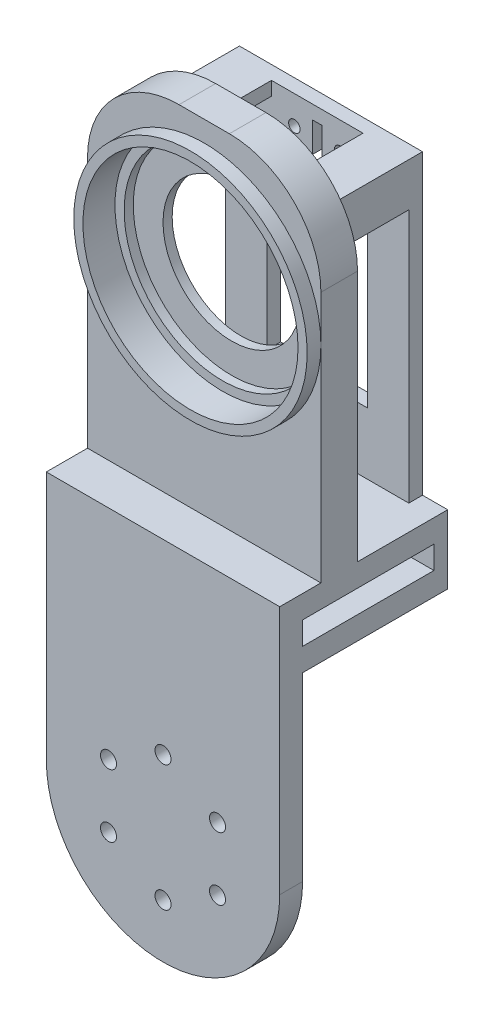
SolidWorks part; units mm, degrees
ref_plane "정면" through (0, 0, 0) normal (0, 0, 1) x (1, 0, 0)
ref_plane "윗면" through (0, 0, 0) normal (0, 1, 0) x (1, 0, 0)
ref_plane "우측면" through (0, 0, 0) normal (1, 0, 0) x (0, 0, -1)
sketch "스케치1" plane through (0, 0, 0) normal (0, 0, 1) x (1, 0, 0)
  line L2 (-25.5, 0) -> (-25.5, 54.5)
  line L3 (-25.5, 54.5) -> (25.5, 54.5)
  line L4 (25.5, 0) -> (25.5, 54.5)
  arc A0 (-25.5, 0) -> (25.5, 0) centre (0, 0) ccw
  dimension "D1" = 51
  dimension "D2" = 54.5
extrude "보스-돌출1" add sketch "스케치1" along normal blind 5
sketch "스케치2" plane through (0, 0, 0) normal (0, 0, -1) x (-1, 0, 0)
  circle A0 centre (0, 0) radius 17.5
  dimension "D1" = 35
extrude "컷-돌출1" cut sketch "스케치2" against normal blind 2
sketch "스케치3" plane through (0, 0, 2) normal (0, 0, -1) x (-1, 0, 0)
  circle A0 centre (0, 0) radius 13.75 construction
  circle A1 centre (0, 13.75) radius 1.75
  circle A2 centre (11.9078, 6.875) radius 1.75
  circle A3 centre (11.9078, -6.875) radius 1.75
  circle A4 centre (0, -13.75) radius 1.75
  circle A5 centre (-11.9078, -6.875) radius 1.75
  circle A6 centre (-11.9078, 6.875) radius 1.75
  point P17 (0, 0)
  dimension "D1" = 27.5
  dimension "D2" = 3.5
  dimension "D3" = 6
extrude "컷-돌출2" cut sketch "스케치3" against normal through all
sketch "스케치4" plane through (0, 0, 0) normal (0, 0, -1) x (-1, 0, 0)
  line L0 (25.5, 54.5) -> (25.5, 0) construction
  line L1 (-25.5, 54.5) -> (25.5, 54.5)
  line L2 (-25.5, 54.5) -> (-25.5, 49.5)
  line L3 (-25.5, 39.5) -> (25.5, 39.5)
  line L4 (25.5, 54.5) -> (25.5, 49.5)
  line L5 (-25.5, 44.5) -> (25.5, 44.5)
  line L6 (-25.5, 49.5) -> (25.5, 49.5)
  line L7 (-25.5, 44.5) -> (-25.5, 39.5)
  line L8 (25.5, 44.5) -> (25.5, 39.5)
  dimension "D1" = 15
  dimension "D2" = 10
  dimension "D3" = 10
extrude "보스-돌출2" add sketch "스케치4" along normal blind 31.7
sketch "스케치12" plane through (0, 54.5, 0) normal (0, 1, 0) x (1, 0, 0)
  line L0 (-25.5, -5) -> (-25.5, 31.7) construction
  line L1 (-25.5, 4) -> (25.5, 4)
  line L2 (-25.5, 4) -> (-25.5, 12)
  line L3 (-25.5, 12) -> (25.5, 12)
  line L4 (25.5, 4) -> (25.5, 12)
  line L5 (25.5, -5) -> (25.5, 31.7) construction
  line L6 (25.5, -5) -> (-25.5, -5) construction
  dimension "D1" = 8
  dimension "D2" = 9
extrude "보스-돌출7" add sketch "스케치12" along normal blind 75
fillet "필렛2" radius 20 2 edges at (-25.5, 129.5, -8) (25.5, 129.5, -8)
sketch "스케치13" plane through (0, 0, -12) normal (0, 0, -1) x (-1, 0, 0)
  line L0 (0, 129.5) -> (0, 54.5) construction
  line L1 (-5.5, 129.5) -> (5.5, 129.5) construction
  line L2 (25.5, 54.5) -> (-25.5, 54.5) construction
  circle A0 centre (0, 99.5) radius 15
  dimension "D1" = 30
  dimension "D2" = 30
extrude "컷-돌출6" cut sketch "스케치13" against normal up to next
sketch "스케치14" plane through (0, 0, -4) normal (0, 0, 1) x (1, 0, 0)
  circle A0 centre (0, 99.5) radius 25.5
extrude "보스-돌출8" add sketch "스케치14" along normal blind 3
sketch "스케치16" plane through (0, 0, -1) normal (0, 0, 1) x (1, 0, 0)
  circle A0 centre (0, 99.5) radius 23.5
  circle A1 centre (0, 99.5) radius 25.5 construction
  dimension "D1" = 2
extrude "컷-돌출7" cut sketch "스케치16" against normal blind 7
sketch "스케치17" plane through (0, 0, -8) normal (0, 0, 1) x (1, 0, 0)
  circle A0 centre (0, 99.5) radius 21.5
  circle A1 centre (0, 99.5) radius 23.5 construction
  dimension "D1" = 2
extrude "컷-돌출8" cut sketch "스케치17" against normal blind 2
sketch "스케치18" plane through (0, 0, -12) normal (0, 0, -1) x (-1, 0, 0)
  line L1 (-20, 79.5) -> (20, 79.5) construction
  line L2 (-20, 79.5) -> (-20, 119.5) construction
  line L3 (-20, 119.5) -> (20, 119.5) construction
  line L4 (20, 79.5) -> (20, 119.5) construction
  line L5 (-20, 119.5) -> (-10, 119.5)
  line L6 (-20, 119.5) -> (-20, 110)
  line L7 (-20, 110) -> (-17, 110)
  line L8 (-10, 119.5) -> (-10, 116.5)
  line L9 (20, 119.5) -> (10, 119.5)
  line L10 (20, 119.5) -> (20, 110)
  line L11 (20, 110) -> (17, 110)
  line L12 (10, 119.5) -> (10, 116.5)
  line L15 (-10, 116.5) -> (-17, 116.5)
  line L16 (-17, 110) -> (-17, 116.5)
  line L19 (10, 116.5) -> (17, 116.5)
  line L20 (17, 110) -> (17, 116.5)
  point P0 (0, 99.5)
  dimension "D1" = 40
  dimension "D2" = 40
  dimension "D3" = 3
  dimension "D4" = 3
  dimension "D5" = 20
  dimension "D6" = 20
extrude "보스-돌출9" add sketch "스케치18" along normal blind 19.7
sketch "스케치19" plane through (0, 0, -31.7) normal (0, 0, -1) x (-1, 0, 0)
  line L0 (-25.5, 54.5) -> (25.5, 54.5) construction
  line L1 (-20, 119.5) -> (20, 119.5)
  line L2 (-20, 119.5) -> (-20, 54.5)
  line L4 (20, 119.5) -> (20, 54.5)
  line L5 (-20, 119.5) -> (-20, 110) construction
  line L6 (20, 110) -> (20, 119.5) construction
  line L7 (20, 54.5) -> (25.5, 54.5)
  line L8 (-25.5, 54.5) -> (-20, 54.5)
  line L9 (-25.5, 54.5) -> (-25.5, 39.5)
  line L10 (-25.5, 39.5) -> (25.5, 39.5)
  line L11 (25.5, 54.5) -> (25.5, 39.5)
extrude "보스-돌출10" add sketch "스케치19" against normal blind 3
sketch "스케치20" plane through (0, 0, -31.7) normal (0, 0, -1) x (-1, 0, 0)
  line L0 (0, 119.5) -> (0, 49.5) construction
  line L1 (20, 119.5) -> (-20, 119.5) construction
  line L2 (-25.5, 49.5) -> (25.5, 49.5) construction
  line L3 (1, 110) -> (11, 110)
  line L4 (-11, 110) -> (-1, 110)
  line L5 (-11, 110) -> (-11, 68)
  line L6 (-11, 68) -> (-1, 68)
  line L7 (11, 110) -> (11, 68)
  line L8 (-11, 110) -> (11, 68) construction
  line L9 (-11, 68) -> (11, 110) construction
  line L10 (-5, 113.35) -> (5, 113.35) construction
  line L11 (-5, 113.35) -> (-5, 64.75) construction
  line L12 (-5, 64.75) -> (5, 64.75) construction
  line L13 (5, 113.35) -> (5, 64.75) construction
  line L14 (-5, 113.35) -> (5, 64.75) construction
  line L15 (-5, 64.75) -> (5, 113.35) construction
  line L16 (-1, 116.5) -> (1, 116.5)
  line L17 (-1, 116.5) -> (-1, 110)
  line L19 (1, 116.5) -> (1, 110)
  line L20 (-1, 116.5) -> (1, 110) construction
  line L21 (-1, 110) -> (1, 116.5) construction
  line L22 (-1, 61.5) -> (1, 61.5)
  line L23 (-1, 61.5) -> (-1, 68)
  line L25 (1, 61.5) -> (1, 68)
  line L26 (-1, 61.5) -> (1, 68) construction
  line L27 (-1, 68) -> (1, 61.5) construction
  line L28 (1, 68) -> (11, 68)
  circle A0 centre (-5, 113.35) radius 1.25
  circle A1 centre (5, 113.35) radius 1.25
  circle A2 centre (-5, 64.75) radius 1.25
  circle A3 centre (5, 64.75) radius 1.25
  point P6 (0, 89)
  point P11 (0, 89.05)
  point P20 (0, 113.25)
  point P25 (0, 64.75)
  dimension "D7" = 2.5
  dimension "D1" = 22
  dimension "D2" = 42
  dimension "D3" = 9.5
  dimension "D4" = 3.35
  dimension "D5" = 3.25
  dimension "D6" = 10
  dimension "D8" = 6.5
  dimension "D9" = 2
  dimension "D10" = 6.5
  dimension "D11" = 2
extrude "컷-돌출9" cut sketch "스케치20" against normal up to next
